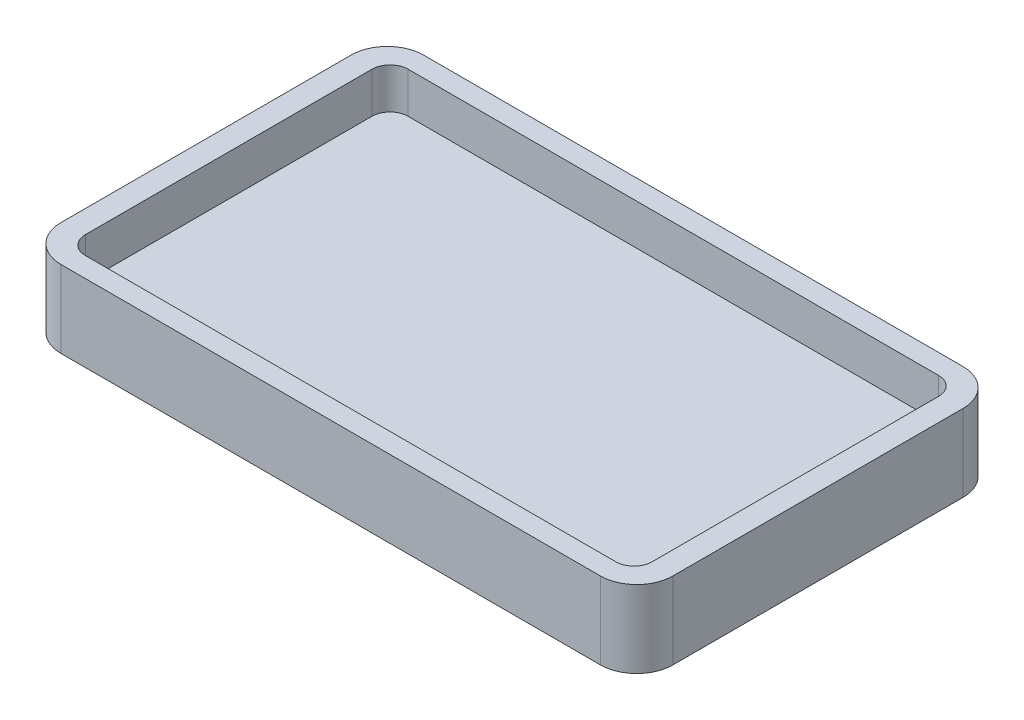
SolidWorks part; units mm, degrees
ref_plane "Front Plane" through (0, 0, 0) normal (0, 0, 1) x (1, 0, 0)
ref_plane "Top Plane" through (0, 0, 0) normal (0, 1, 0) x (1, 0, 0)
ref_plane "Right Plane" through (0, 0, 0) normal (1, 0, 0) x (0, 0, -1)
sketch "Sketch1" plane through (0, 0, 0) normal (0, 1, 0) x (1, 0, 0)
  line L1 (-85.725, 50.8) -> (85.725, 50.8)
  line L2 (-85.725, 50.8) -> (-85.725, -50.8)
  line L3 (-85.725, -50.8) -> (85.725, -50.8)
  line L4 (85.725, 50.8) -> (85.725, -50.8)
  point P4 (0, 50.8)
  point P6 (-85.725, 0)
  dimension "D1" = 101.6
  dimension "D2" = 171.45
extrude "Boss-Extrude1" add sketch "Sketch1" along normal blind 21.59
sketch "Sketch2" plane through (0, 21.59, 0) normal (0, 1, 0) x (1, 0, 0)
  line L1 (-79.375, 45.212) -> (79.375, 45.212)
  line L2 (-79.375, 45.212) -> (-79.375, -45.212)
  line L3 (-79.375, -45.212) -> (79.375, -45.212)
  line L4 (79.375, 45.212) -> (79.375, -45.212)
  point P4 (-79.375, 0)
  point P6 (0, 45.212)
  dimension "D1" = 90.424
  dimension "D2" = 158.75
extrude "Cut-Extrude1" cut sketch "Sketch2" against normal blind 11.43
fillet "Fillet1" radius 5.08 4 edges at (79.375, 15.875, -45.212) (79.375, 15.875, 45.212) (-79.375, 15.875, 45.212) (-79.375, 15.875, -45.212)
fillet "Fillet2" radius 10.16 4 edges at (-85.725, 10.795, -50.8) (85.725, 10.795, -50.8) (85.725, 10.795, 50.8) (-85.725, 10.795, 50.8)
